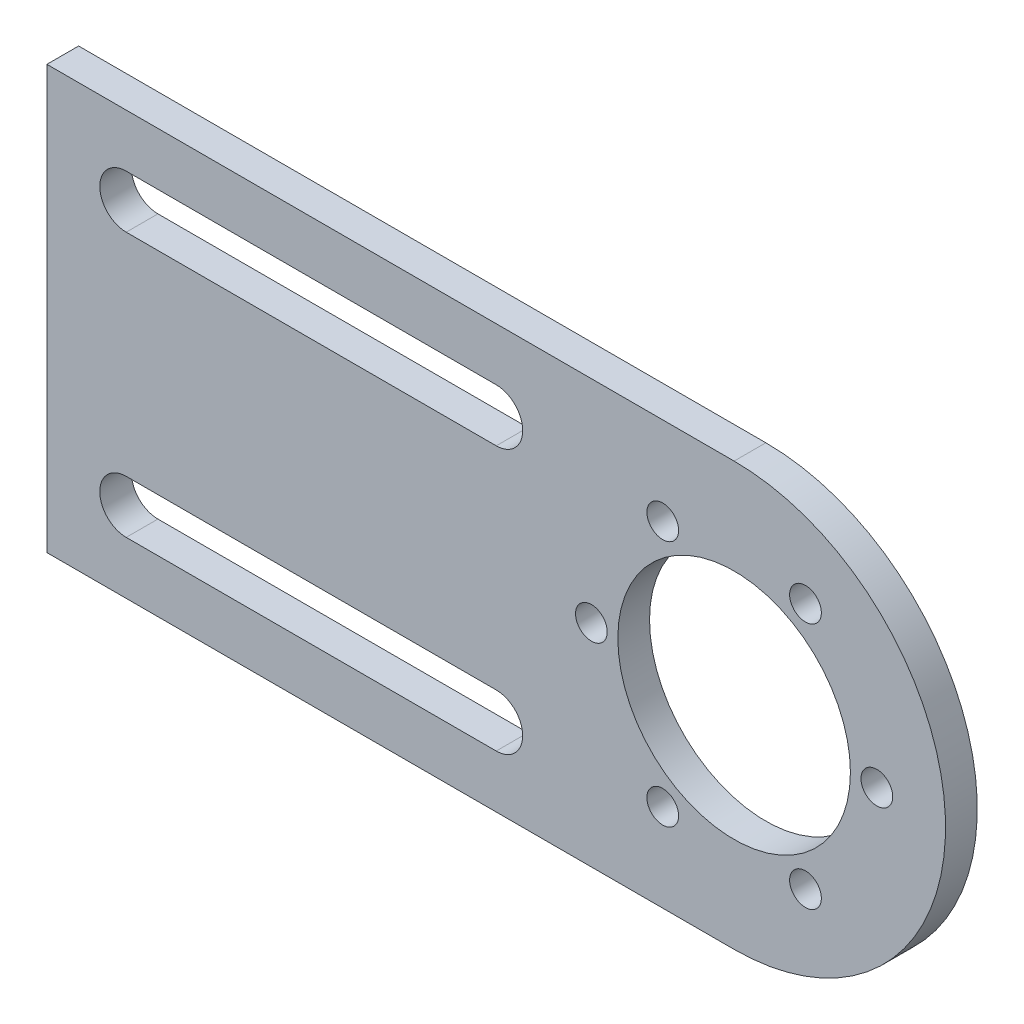
SolidWorks part; units mm, degrees
ref_plane "Front" through (0, 0, 0) normal (0, 0, 1) x (1, 0, 0)
ref_plane "Top" through (0, 0, 0) normal (0, 1, 0) x (1, 0, 0)
ref_plane "Right" through (0, 0, 0) normal (1, 0, 0) x (0, 0, -1)
sketch "Sketch1" plane through (0, 0, 0) normal (0, 0, 1) x (1, 0, 0)
  line L0 (-25, 15) -> (10, 15)
  line L1 (32.5, 20) -> (-32.5, 20)
  line L3 (32.5, -20) -> (-32.5, -20)
  line L4 (-32.5, 20) -> (-32.5, -20)
  line L5 (32.5, 20) -> (-32.5, -20) construction
  line L6 (32.5, -20) -> (-32.5, 20) construction
  line L7 (10, 10) -> (-25, 10)
  line L10 (-25, -10) -> (10, -10)
  line L11 (10, -15) -> (-25, -15)
  arc A0 (32.5, 20) -> (32.5, -20) centre (32.5, 0) cw
  circle A1 centre (32.5, 0) radius 11
  arc A3 (10, 15) -> (10, 10) centre (10, 12.5) cw
  arc A4 (-25, 10) -> (-25, 15) centre (-25, 12.5) cw
  arc A7 (10, -10) -> (10, -15) centre (10, -12.5) cw
  arc A8 (-25, -15) -> (-25, -10) centre (-25, -12.5) cw
  point P0 (0, 0)
  point P14 (7.3041, 9.94)
  point P21 (0, 0)
  point P22 (3.6318, -12.5)
  dimension "D3" = 22
  dimension "D4" = 35
  dimension "D5" = 2.5
  dimension "D8" = 2.5
  dimension "D1" = 40
  dimension "D2" = 65
  dimension "D6" = 7.5
  dimension "D7" = 25
  dimension "D9" = 5
  dimension "D10" = 35
extrude "Boss-Extrude1" add sketch "Sketch1" along normal blind 3
sketch "Sketch2" plane through (0, 0, 3) normal (0, 0, 1) x (1, 0, 0)
  circle A1 centre (46, 0) radius 1.5
  circle A2 centre (32.5, 0) radius 11 construction
  dimension "D1" = 3
  dimension "D2" = 13.5
extrude "Cut-Extrude1" cut sketch "Sketch2" against normal up to surface (3 mm away) up to face at (-7.5, 12.5, 0)
pattern_circular "CirPattern1" count 6 over 360 about axis through (32.5, 0, 0) along (0, 0, 1) of "Cut-Extrude1"
